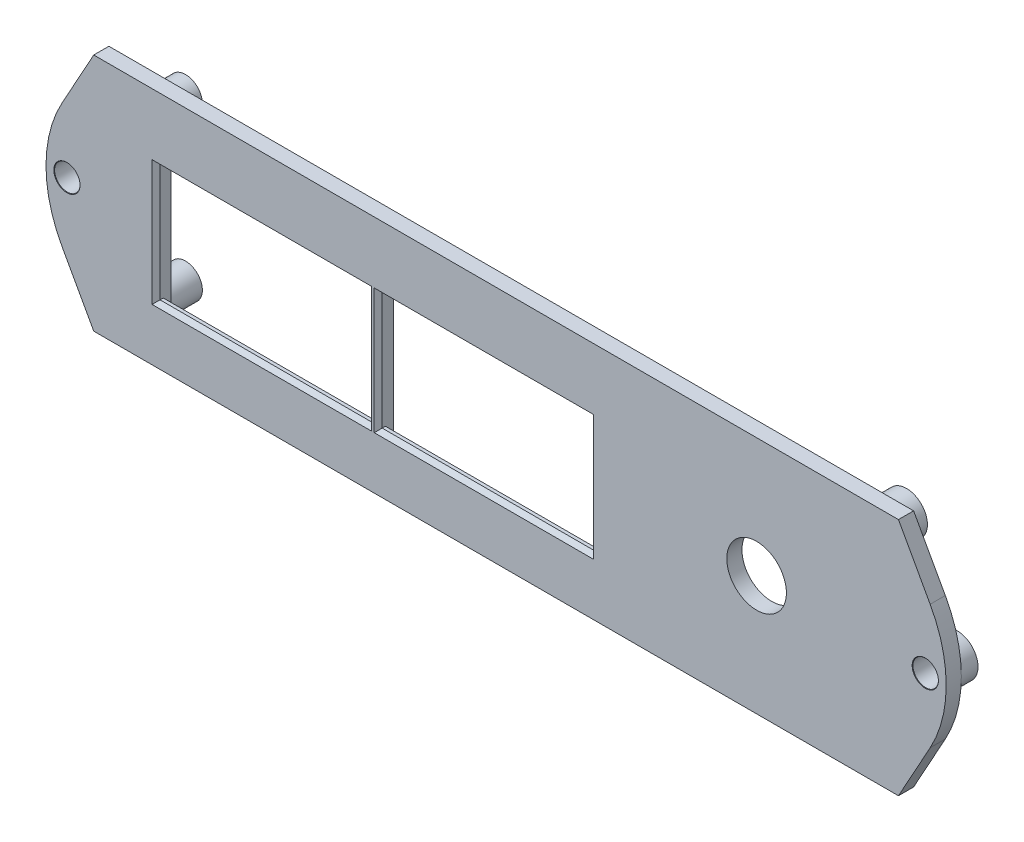
SolidWorks part; units mm, degrees
ref_plane "Front Plane" through (0, 0, 0) normal (0, 0, 1) x (1, 0, 0)
ref_plane "Top Plane" through (0, 0, 0) normal (0, 1, 0) x (1, 0, 0)
ref_plane "Right Plane" through (0, 0, 0) normal (1, 0, 0) x (0, 0, -1)
sketch "Sketch1" plane through (0, 0, 0) normal (0, 0, 1) x (1, 0, 0)
  line L10 (-50.6, 15.04) -> (50.6, 15.04)
  line L11 (50.6, 15.04) -> (54.5903, 7.8135)
  line L12 (54.5903, -7.8135) -> (50.6, -15.04)
  line L13 (50.6, -15.04) -> (-50.6, -15.04)
  line L14 (-50.6, -15.04) -> (-54.5903, -7.8135)
  line L15 (-54.5903, 7.8135) -> (-50.6, 15.04)
  line L16 (-50.6, 15.04) -> (-50.6, -15.04) construction
  line L18 (50.6, 15.04) -> (50.6, -15.04) construction
  arc A4 (54.5903, 7.8135) -> (54.5903, -7.8135) centre (40.44, 0) cw
  arc A5 (-54.5903, -7.8135) -> (-54.5903, 7.8135) centre (-40.44, 0) cw
  point P5 (0, 15.04)
  dimension "D1" = 10.16
  dimension "D3" = 8.255
  dimension "D4" = 101.2
  dimension "D5" = 30.08
extrude "Boss-Extrude1" add sketch "Sketch1" along normal blind 1.905
sketch "Sketch6" plane through (0, 0, 0) normal (0, 0, -1) x (-1, 0, 0)
  circle A0 centre (-53.975, 0) radius 2.6292
  circle A1 centre (53.975, 0) radius 2.6292
  arc A2 (-54.5903, 7.8135) -> (-54.5903, -7.8135) centre (-40.44, 0) ccw construction
  arc A3 (54.5903, -7.8135) -> (54.5903, 7.8135) centre (40.44, 0) ccw construction
  dimension "D1" = 107.95
extrude "Boss-Extrude4" add sketch "Sketch6" along normal offset from surface (2.095 mm away) 4 up to face at (0, 0, 1.905)
sketch "Sketch2" plane through (0, 0, 1.905) normal (0, 0, 1) x (1, 0, 0)
  line L0 (-53.975, 0) -> (53.975, 0) construction
  point P3 (0, 0)
  point P5 (-53.975, 0)
  point P6 (53.975, 0)
  dimension "D1" = 107.95
hole_wizard "Ø3.0mm Dowel Hole1" positions "Sketch2" profile "Sketch3" hole size "Ø3.0" standard "ANSI Metric" end condition through all
sketch "Sketch3" plane through (53.975, 0, 1.905) normal (1, 0, 0) x (0, -1, 0)
  line L0 (0, 0) -> (0, 4)
  line L1 (0, 4) -> (1.6, 4)
  line L2 (1.6, 4) -> (1.6, 0.05)
  line L3 (1.6, 0.05) -> (1.65, 0)
  line L5 (1.65, 0) -> (0, 0)
  line L6 (-1.6, 0.05) -> (-1.65, 0) construction
  line L11 (0, -6.35) -> (0, 107.95) construction
  dimension "Thru Hole Dia." = 3.2
  dimension "Thru Hole Depth" = 4
  dimension "Near C'Sink Dia." = 3.3
  dimension "Near C'Sink Angle" = 90
sketch "Sketch7" plane through (0, 0, 1.905) normal (0, 0, 1) x (1, 0, 0)
  line L0 (-15.614, 11.26) -> (-43.314, 11.26) construction
  line L1 (-42.764, 6.81) -> (-16.164, 6.81)
  line L2 (-42.764, 6.81) -> (-42.764, -7.9601)
  line L3 (-42.764, -7.9601) -> (-16.164, -7.9601)
  line L4 (-16.164, 6.81) -> (-16.164, -7.9601)
  line L5 (-14.824, 6.81) -> (11.776, 6.81)
  line L6 (-14.824, 6.81) -> (-14.824, -7.9601)
  line L7 (-14.824, -7.9601) -> (11.776, -7.9601)
  line L8 (11.776, 6.81) -> (11.776, -7.9601)
  line L9 (-43.264, 11.31) -> (-43.264, -16.39) construction
  line L10 (-43.314, -16.34) -> (-15.614, -16.34) construction
  line L11 (-15.664, 11.31) -> (-15.664, -16.39) construction
  line L12 (-15.324, 11.31) -> (-15.324, -16.39) construction
  line L13 (32.702, 0.06) -> (32.822, -0.06) construction
  line L14 (32.822, 0.06) -> (32.702, -0.06) construction
  circle A0 centre (32.762, 0) radius 3.75
  point P15 (-29.464, 11.26)
  point P16 (-29.464, 6.81)
  point P26 (32.762, 0)
  point P27 (32.762, 0)
  dimension "D6" = 7.5
  dimension "D1" = 4.45
  dimension "D2" = 0.5
  dimension "D3" = 14.7701
  dimension "D4" = 14.7701
  dimension "D5" = 0.5
extrude "Cut-Extrude1" cut sketch "Sketch7" against normal through all
sketch "Sketch9" plane through (0, 0, 0) normal (0, 0, -1) x (-1, 0, 0)
  circle A0 centre (-45.212, 9.906) radius 2.6292
  circle A1 centre (-45.212, -10.16) radius 2.6292
  circle A2 centre (45.466, -10.16) radius 2.125
  circle A3 centre (45.466, 10.16) radius 2.125
  circle A4 centre (-53.975, 0) radius 2.6292 construction
  point P8 (0, 0)
  point P9 (0, 0)
  point P10 (0, 0)
  point P11 (0, 0)
  point P12 (0, 0)
  dimension "D1" = 4.25
extrude "Boss-Extrude5" add sketch "Sketch9" along normal blind 4.5
sketch "Sketch10" plane through (0, 0, -4.5) normal (0, 0, -1) x (-1, 0, 0)
  circle A0 centre (-45.212, 9.906) radius 2.6292 construction
  circle A1 centre (-45.212, -10.16) radius 2.6292 construction
  circle A2 centre (45.466, 10.16) radius 2.125 construction
  circle A3 centre (45.466, -10.16) radius 2.125 construction
  point P0 (-45.212, 9.906)
  point P1 (-45.212, -10.16)
  point P2 (45.466, -10.16)
  point P3 (45.466, 10.16)
  point P4 (-45.212, 9.906)
  point P5 (-45.212, -10.16)
  point P6 (0, 0)
  point P9 (0, 0)
  point P12 (0, 0)
  point P15 (0, 0)
hole_wizard "Ø3.0mm Dowel Hole2" positions "Sketch10" profile "Sketch11" hole size "Ø3.0" standard "ANSI Metric"
sketch "Sketch11" plane through (45.212, 9.906, -4.5) normal (1, 0, 0) x (0, 1, 0)
  line L0 (0, 0) -> (0, 4.9313)
  line L1 (0, 4.9313) -> (1.55, 4)
  line L2 (1.55, 4) -> (1.55, 0.1)
  line L3 (1.55, 0.1) -> (1.65, 0)
  line L5 (1.65, 0) -> (0, 0)
  line L6 (-1.55, 0.1) -> (-1.65, 0) construction
  line L10 (0, 4.9313) -> (-1.55, 4) construction
  line L11 (0, -6.35) -> (0, 107.95) construction
  dimension "Hole Dia." = 3.1
  dimension "Hole Depth" = 4
  dimension "Near C'Sink Dia." = 3.3
  dimension "Near C'Sink Angle" = 90
  dimension "Drill Angle" = 118
sketch "Sketch12" plane through (0, 0, 0) normal (0, 0, -1) x (-1, 0, 0)
  line L0 (-11.776, 6.81) -> (-11.776, -7.9601) construction
  line L1 (-11.776, 12.11) -> (14.824, 12.11)
  line L2 (-11.776, 12.11) -> (-11.776, -13.2601)
  line L3 (-11.776, -13.2601) -> (14.824, -13.2601)
  line L4 (14.824, 12.11) -> (14.824, -13.2601)
  line L5 (14.824, -7.9601) -> (14.824, 6.81) construction
  line L6 (16.164, 6.81) -> (16.164, -7.9601) construction
  line L7 (42.764, -7.9601) -> (42.764, 6.81) construction
  line L8 (-11.776, -7.9601) -> (14.824, -7.9601) construction
  line L9 (16.164, 12.11) -> (42.764, 12.11)
  line L10 (16.164, 12.11) -> (16.164, -13.2601)
  line L11 (16.164, -13.2601) -> (42.764, -13.2601)
  line L12 (42.764, 12.11) -> (42.764, -13.2601)
  line L13 (14.824, 6.81) -> (-11.776, 6.81) construction
  point P4 (0, 0)
  point P5 (42.764, 6.81)
  point P10 (0, 0)
  point P11 (0, 0)
  point P12 (0, 0)
  point P13 (-9.5885, 6.81)
  point P24 (-11.776, 11.3022)
  dimension "D1" = 5.3
  dimension "D2" = 5.3
extrude "Cut-Extrude2" cut sketch "Sketch12" against normal blind 1
chamfer "Chamfer1" distance 0.5 angle 45 8 edges at (11.776, -0.575, 1.905) (-1.524, -7.9601, 1.905) (-1.524, 6.81, 1.905) (-14.824, -0.575, 1.905) (-16.164, -0.575, 1.905) (-29.464, -7.9601, 1.905) (-42.764, -0.575, 1.905) (-29.464, 6.81, 1.905)
